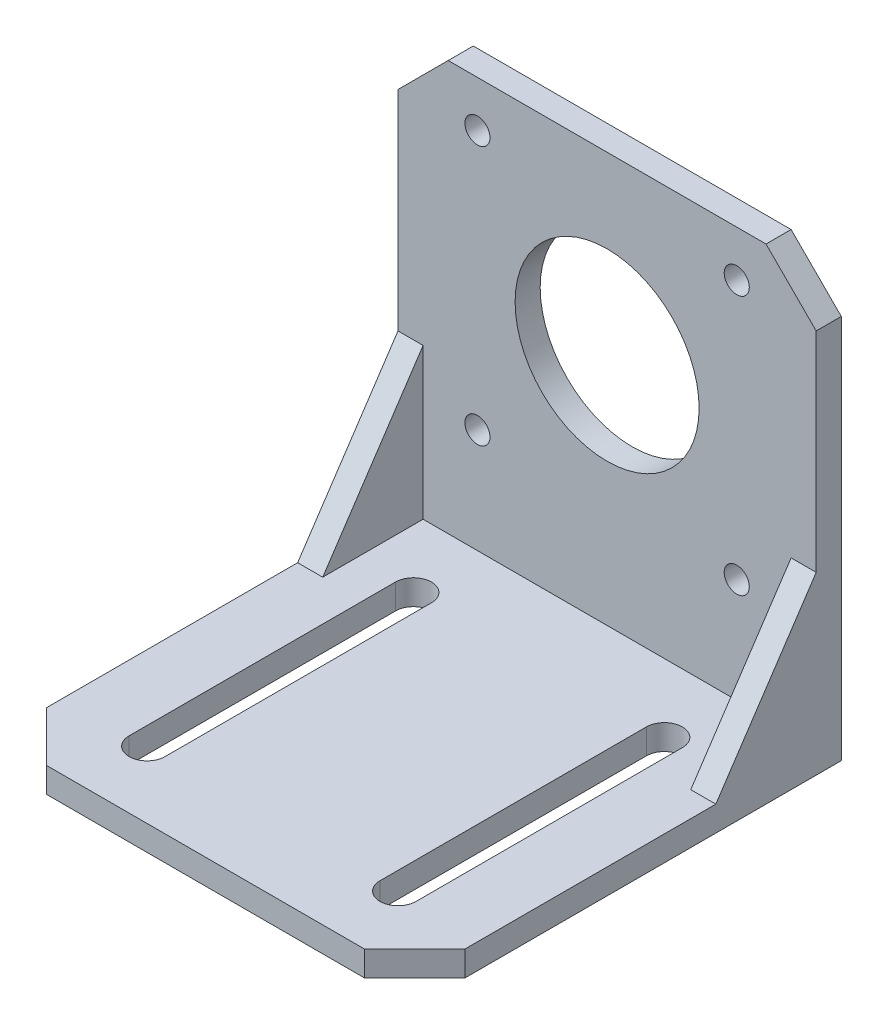
SolidWorks part; units mm, degrees
ref_plane "Front Plane" through (0, 0, 0) normal (0, 0, 1) x (1, 0, 0)
ref_plane "Top Plane" through (0, 0, 0) normal (0, 1, 0) x (1, 0, 0)
ref_plane "Right Plane" through (0, 0, 0) normal (1, 0, 0) x (0, 0, -1)
sketch "Sketch1" plane through (0, 0, 0) normal (0, 0, 1) x (1, 0, 0)
  line L0 (-25, -21) -> (25, -21) construction
  line L1 (-25, 21) -> (25, 21)
  line L2 (-25, 21) -> (-25, -21)
  line L4 (25, 21) -> (25, -21)
  line L5 (-25, 21) -> (25, -21) construction
  line L6 (-25, -21) -> (25, 21) construction
  line L7 (-15.5, 15.5) -> (15.5, 15.5) construction
  line L8 (-15.5, 15.5) -> (-15.5, -15.5) construction
  line L9 (-15.5, -15.5) -> (15.5, -15.5) construction
  line L10 (15.5, 15.5) -> (15.5, -15.5) construction
  line L11 (-15.5, 15.5) -> (15.5, -15.5) construction
  line L12 (-15.5, -15.5) -> (15.5, 15.5) construction
  line L14 (-25, -21) -> (-25, -31)
  line L15 (-25, -31) -> (25, -31)
  line L16 (25, -21) -> (25, -31)
  circle A0 centre (0, 0) radius 11
  circle A1 centre (-15.5, 15.5) radius 1.5
  circle A2 centre (15.5, 15.5) radius 1.5
  circle A3 centre (-15.5, -15.5) radius 1.5
  circle A4 centre (15.5, -15.5) radius 1.5
  point P0 (0, 0)
  dimension "D3" = 22
  dimension "D6" = 3
  dimension "D7" = 3
  dimension "D8" = 3
  dimension "D9" = 3
  dimension "D1" = 50
  dimension "D2" = 42
  dimension "D4" = 31
  dimension "D5" = 31
  dimension "D10" = 52
extrude "Boss-Extrude1" add sketch "Sketch1" along normal blind 3
sketch "Sketch2" plane through (0, 0, 3) normal (0, 0, 1) x (1, 0, 0)
  line L0 (-25, 21) -> (-25, -31) construction
  line L1 (-25, -28) -> (25, -28)
  line L2 (-25, -28) -> (-25, -31)
  line L3 (-25, -31) -> (25, -31)
  line L4 (25, -28) -> (25, -31)
  dimension "D1" = 3
extrude "Boss-Extrude2" add sketch "Sketch2" along normal blind 48
sketch "Sketch3" plane through (0, -31, 0) normal (0, -1, 0) x (1, 0, 0)
  line L0 (0, 24.9363) -> (0, 0) construction
  line L1 (-15, 43) -> (-15, 11.15) construction
  line L2 (-12.85, 43) -> (-12.85, 11.15)
  line L3 (-17.15, 43) -> (-17.15, 11.15)
  line L5 (15, 43) -> (15, 11.15) construction
  line L6 (12.85, 43) -> (12.85, 11.15)
  line L7 (17.15, 43) -> (17.15, 11.15)
  line L8 (-25, 0) -> (25, 0) construction
  arc A0 (-12.85, 43) -> (-17.15, 43) centre (-15, 43) ccw
  arc A1 (-17.15, 11.15) -> (-12.85, 11.15) centre (-15, 11.15) ccw
  arc A2 (12.85, 43) -> (17.15, 43) centre (15, 43) cw
  arc A3 (17.15, 11.15) -> (12.85, 11.15) centre (15, 11.15) cw
  point P2 (15, 9)
  point P5 (-15, 27.075)
  point P14 (15, 27.075)
  dimension "D4" = 34
  dimension "D1" = 4.3
  dimension "D2" = 30
  dimension "D3" = 9
extrude "Cut-Extrude1" cut sketch "Sketch3" against normal up to next
sketch "Sketch4" plane through (0, 0, 0) normal (1, 0, 0) x (0, 0, -1)
  line L0 (-3, -28) -> (-3, -10)
  line L1 (-3, -28) -> (-3, 21) construction
  line L2 (-3, -10) -> (-15, -28)
  line L3 (-51, -28) -> (-3, -28) construction
  line L4 (-15, -28) -> (-3, -28)
  dimension "D1" = 18
  dimension "D2" = 12
extrude "Boss-Extrude3" add sketch "Sketch4" along normal blind 3 from offset 22
pattern_linear "LPattern2" count 2 spacing 47 along (-1, 0, 0) of "Boss-Extrude3"
sketch "Sketch5" plane through (0, 0, 0) normal (0, 0, -1) x (-1, 0, 0)
  line L0 (-19, 21) -> (-25, 15)
  line L1 (-25, 21) -> (25, 21) construction
  line L2 (-25, -31) -> (-25, 21) construction
  line L3 (-25, 21) -> (-25, 15)
  line L4 (-25, 21) -> (-19, 21)
  line L5 (0, 0) -> (0, 6.0869) construction
  line L6 (25, 21) -> (19, 21)
  line L7 (25, 21) -> (25, 15)
  line L8 (19, 21) -> (25, 15)
  dimension "D1" = 6
  dimension "D2" = 6
extrude "Cut-Extrude2" cut sketch "Sketch5" against normal up to next
sketch "Sketch6" plane through (0, -31, 0) normal (0, -1, 0) x (1, 0, 0)
  line L0 (-25, 51) -> (-25, 45)
  line L1 (-25, 51) -> (-25, 0) construction
  line L2 (-25, 45) -> (-19, 51)
  line L3 (-25, 51) -> (25, 51) construction
  line L4 (-25, 51) -> (-19, 51)
  line L5 (0, 0) -> (0, 10.6257) construction
  line L6 (25, 51) -> (19, 51)
  line L7 (25, 45) -> (19, 51)
  line L8 (25, 51) -> (25, 45)
  dimension "D1" = 6
  dimension "D2" = 6
extrude "Cut-Extrude3" cut sketch "Sketch6" against normal up to next
